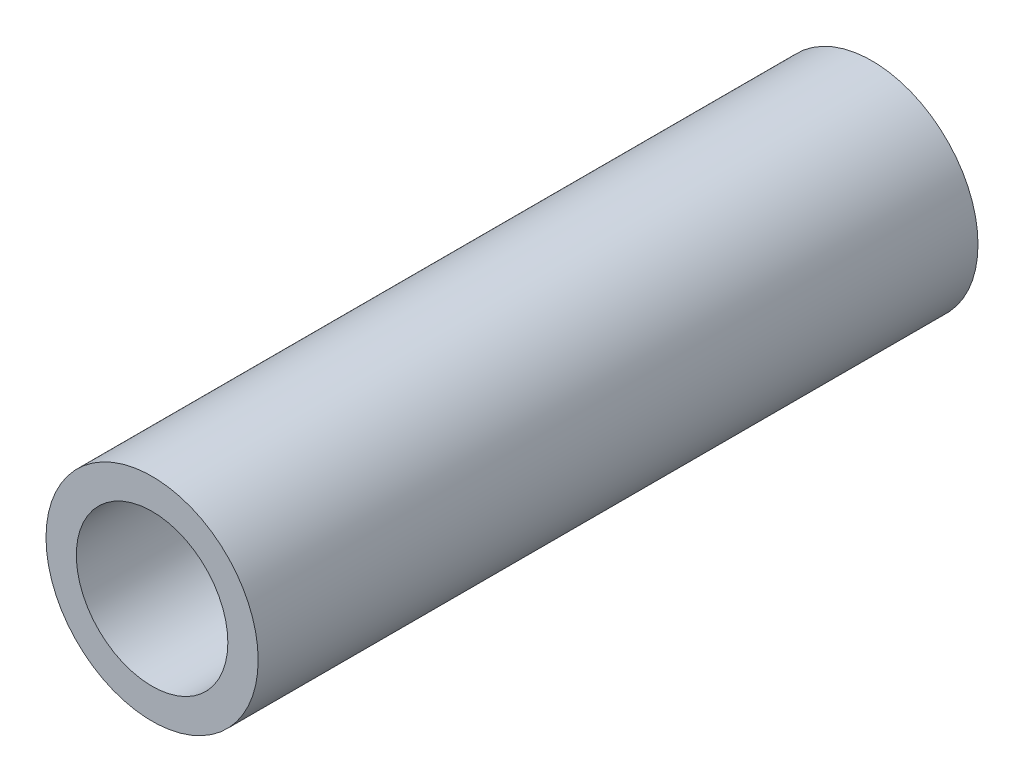
SolidWorks part; units mm, degrees
ref_plane "Front Plane" through (0, 0, 0) normal (0, 0, 1) x (1, 0, 0)
ref_plane "Top Plane" through (0, 0, 0) normal (0, 1, 0) x (1, 0, 0)
ref_plane "Right Plane" through (0, 0, 0) normal (1, 0, 0) x (0, 0, -1)
sketch "Sketch1" plane through (0, 0, 0) normal (0, 0, 1) x (1, 0, 0)
  circle A0 centre (0, 0) radius 10
  circle A1 centre (0, 0) radius 14
  dimension "D1" = 20
  dimension "D2" = 4
extrude "Boss-Extrude1" add sketch "Sketch1" along normal blind 95
